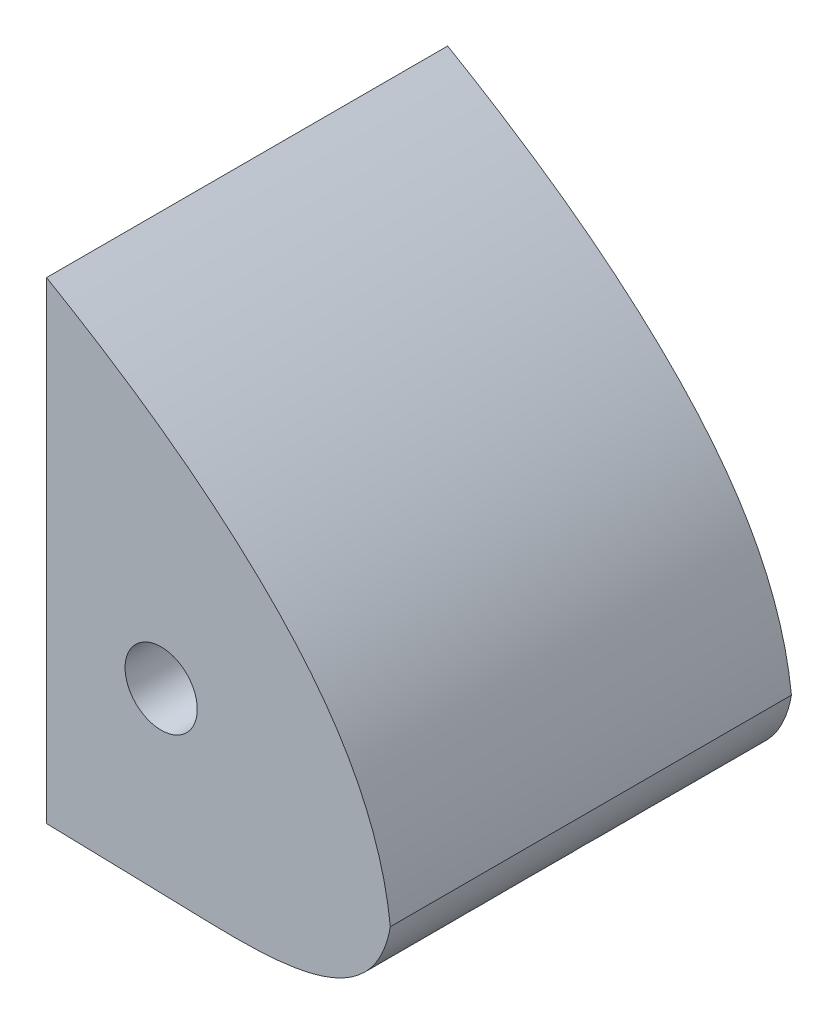
SolidWorks part; units mm, degrees
ref_plane "Front Plane" through (0, 0, 0) normal (0, 0, 1) x (1, 0, 0)
ref_plane "Top Plane" through (0, 0, 0) normal (0, 1, 0) x (1, 0, 0)
ref_plane "Right Plane" through (0, 0, 0) normal (1, 0, 0) x (0, 0, -1)
sketch "Sketch1" plane through (0, 0, 0) normal (0, 0, 1) x (1, 0, 0)
  line L0 (-66.007, 14.9523) -> (-66.007, -5.6347)
  circle A0 centre (63.517, -7.2283) radius 2
  circle A1 centre (-25.383, 13.0917) radius 2.127
  spline S0 degree 3 poles (76.217, -12.3083) (75.607, -6.7666) (69.7043, 1.1384) (56.4222, 10.2644) (36.9761, 19.3708) (8.7417, 24.8154) (-27.4552, 23.5667) (-52.3876, 18.1036) (-66.007, 14.9523) knots 0 0 0 0 0.086587 0.161737 0.268322 0.445157 0.638029 0.872371 0.872371 0.872371 0.872371
  spline S1 degree 3 poles (-66.007, -5.6347) (-44.594, -5.5392) (-13.013, -6.7241) (26.1367, -12.7509) (48.7653, -16.9008) (64.6834, -16.9691) (75.2906, -17.5225) (76.217, -12.3083) knots 0.133251 0.133251 0.133251 0.133251 0.51733 0.696667 0.84941 0.91952 1 1 1 1
  dimension "D2" = 4
  dimension "D1" = 142.224
extrude "Boss-Extrude1" add sketch "Sketch1" along normal blind 22.225
sketch "Sketch2" plane through (0, 0, 22.225) normal (0, 0, 1) x (1, 0, 0)
  line L0 (-66.007, 14.9523) -> (-66.007, -5.6347) construction
  line L1 (-77.1256, 30.6925) -> (57.167, 30.6925)
  line L2 (-77.1256, 30.6925) -> (-77.1256, -22.6703)
  line L3 (-77.1256, -22.6703) -> (57.167, -22.6703)
  line L4 (57.167, 30.6925) -> (57.167, -22.6703)
  dimension "D1" = 11.1187
  dimension "D2" = 19.05
extrude "Cut-Extrude1" cut sketch "Sketch2" against normal blind 28.956
